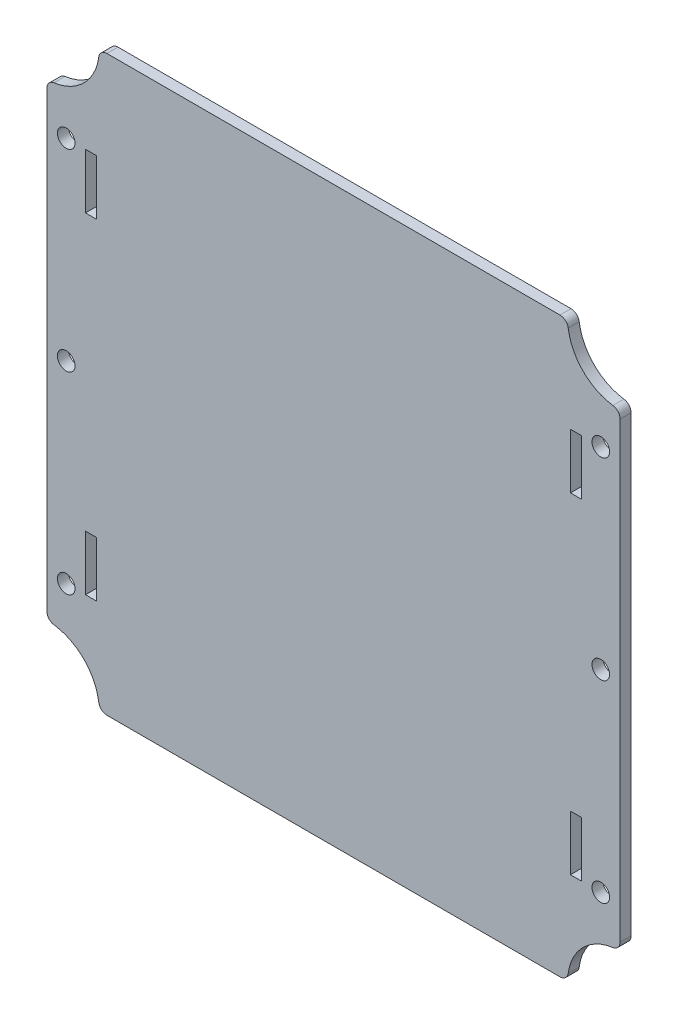
SolidWorks part; units mm, degrees
ref_plane "Alzado" through (0, 0, 0) normal (0, 0, 1) x (1, 0, 0)
ref_plane "Planta" through (0, 0, 0) normal (0, 1, 0) x (1, 0, 0)
ref_plane "Vista lateral" through (0, 0, 0) normal (1, 0, 0) x (0, 0, -1)
sketch "Croquis1" plane through (0, 0, 0) normal (0, 0, 1) x (1, 0, 0)
  line L0 (10.8972, 0) -> (93.1028, 0)
  line L1 (104, 10.8972) -> (104, 93.1028)
  line L2 (93.1028, 104) -> (10.8972, 104)
  line L3 (0, 93.1028) -> (0, 10.8972)
  line L4 (0, 52) -> (104, 52) construction
  line L5 (52, 104) -> (52, 0) construction
  line L6 (3.5, 52) -> (3.5, 87) construction
  line L7 (7, 104) -> (7, 0) construction
  line L8 (7, 87) -> (9, 87)
  line L9 (9, 87) -> (9, 77)
  line L10 (9, 77) -> (7, 77)
  line L11 (7, 77) -> (7, 87)
  line L12 (95, 77) -> (97, 77)
  line L13 (95, 87) -> (95, 77)
  line L14 (97, 87) -> (95, 87)
  line L15 (97, 77) -> (97, 87)
  line L16 (95, 17) -> (95, 27)
  line L17 (97, 17) -> (95, 17)
  line L18 (97, 27) -> (97, 17)
  line L19 (95, 27) -> (97, 27)
  line L20 (9, 27) -> (7, 27)
  line L21 (9, 17) -> (9, 27)
  line L22 (7, 17) -> (9, 17)
  line L23 (7, 27) -> (7, 17)
  circle A0 centre (3.5, 52) radius 1.6
  circle A1 centre (3.5, 87) radius 1.6
  circle A2 centre (3.5, 17) radius 1.6
  circle A3 centre (100.5, 17) radius 1.6
  circle A4 centre (100.5, 52) radius 1.6
  circle A5 centre (100.5, 87) radius 1.6
  arc A7 (94.5887, 102.7045) -> (102.7045, 94.5887) centre (104, 104) ccw
  arc A8 (9.4113, 102.7045) -> (1.2955, 94.5887) centre (0, 104) cw
  arc A9 (94.5887, 1.2955) -> (102.7045, 9.4113) centre (104, 0) cw
  arc A10 (9.4113, 1.2955) -> (1.2955, 9.4113) centre (0, 0) ccw
  arc A11 (0, 93.1028) -> (1.2955, 94.5887) centre (1.5, 93.1028) cw
  arc A12 (9.4113, 102.7045) -> (10.8972, 104) centre (10.8972, 102.5) cw
  arc A13 (94.5887, 102.7045) -> (93.1028, 104) centre (93.1028, 102.5) ccw
  arc A14 (102.7045, 9.4113) -> (104, 10.8972) centre (102.5, 10.8972) ccw
  arc A15 (104, 93.1028) -> (102.7045, 94.5887) centre (102.5, 93.1028) ccw
  arc A16 (1.2955, 9.4113) -> (0, 10.8972) centre (1.5, 10.8972) cw
  arc A17 (9.4113, 1.2955) -> (10.8972, 0) centre (10.8972, 1.5) ccw
  arc A18 (94.5887, 1.2955) -> (93.1028, 0) centre (93.1028, 1.5) cw
  dimension "D3" = 3.5
  dimension "D4" = 3.2
  dimension "D6" = 3.2
  dimension "D7" = 104
  dimension "D8" = 19
  dimension "D10" = 82.2055
  dimension "D11" = 1.5
  dimension "D12" = 82.2055
  dimension "D13" = 1.5
  dimension "D14" = 7
  dimension "D15" = 1.5
  dimension "D16" = 2
  dimension "D17" = 1.5
  dimension "D1" = 104
  dimension "D2" = 104
  dimension "D5" = 35
  dimension "D9" = 104
  dimension "D18" = 10
extrude "Saliente-Extruir1" add sketch "Croquis1" against normal blind 2
